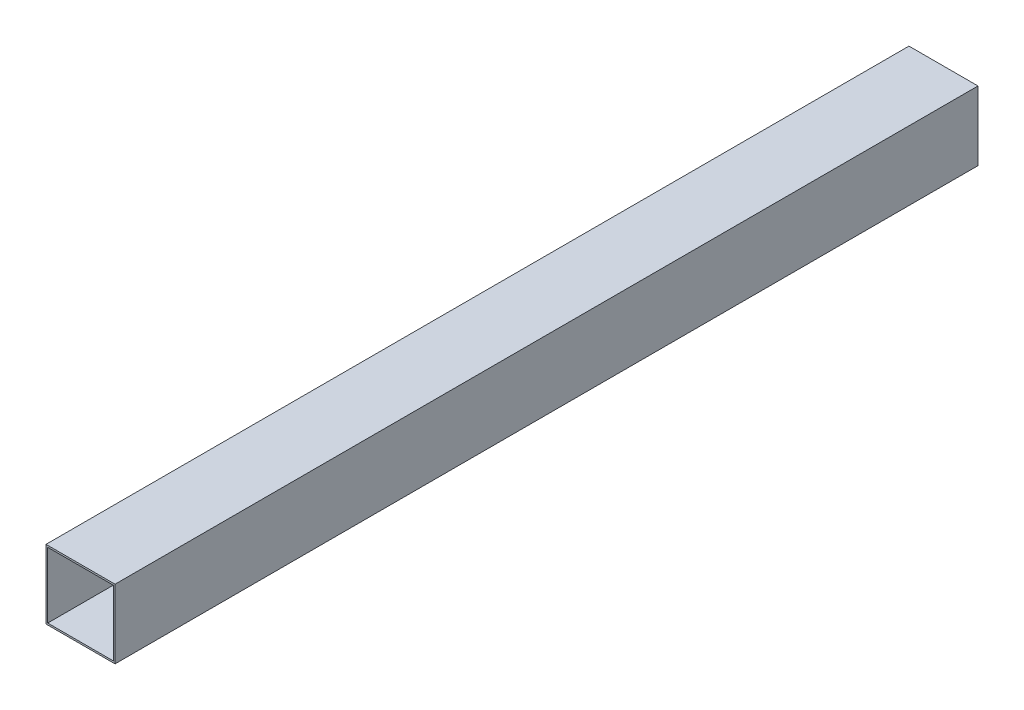
SolidWorks part; units mm, degrees
ref_plane "Płaszczyzna przednia" through (0, 0, 0) normal (0, 0, 1) x (1, 0, 0)
ref_plane "Płaszczyzna górna" through (0, 0, 0) normal (0, 1, 0) x (1, 0, 0)
ref_plane "Płaszczyzna prawa" through (0, 0, 0) normal (1, 0, 0) x (0, 0, -1)
sketch "Szkic1" plane through (0, 0, 0) normal (0, 0, 1) x (1, 0, 0)
  line L1 (0, 29.5229) -> (40, 29.5229)
  line L2 (0, 29.5229) -> (0, -10.4771)
  line L3 (0, -10.4771) -> (40, -10.4771)
  line L4 (40, 29.5229) -> (40, -10.4771)
  line L5 (1, 28.5229) -> (39, 28.5229)
  line L6 (1, 28.5229) -> (1, -9.4771)
  line L7 (1, -9.4771) -> (39, -9.4771)
  line L8 (39, 28.5229) -> (39, -9.4771)
  dimension "D1" = 40
  dimension "D2" = 40
  dimension "D3" = 1
  dimension "D4" = 1
  dimension "D5" = 1
  dimension "D6" = 1
extrude "Dodanie-wyciągnięcie1" add sketch "Szkic1" along normal blind 500
